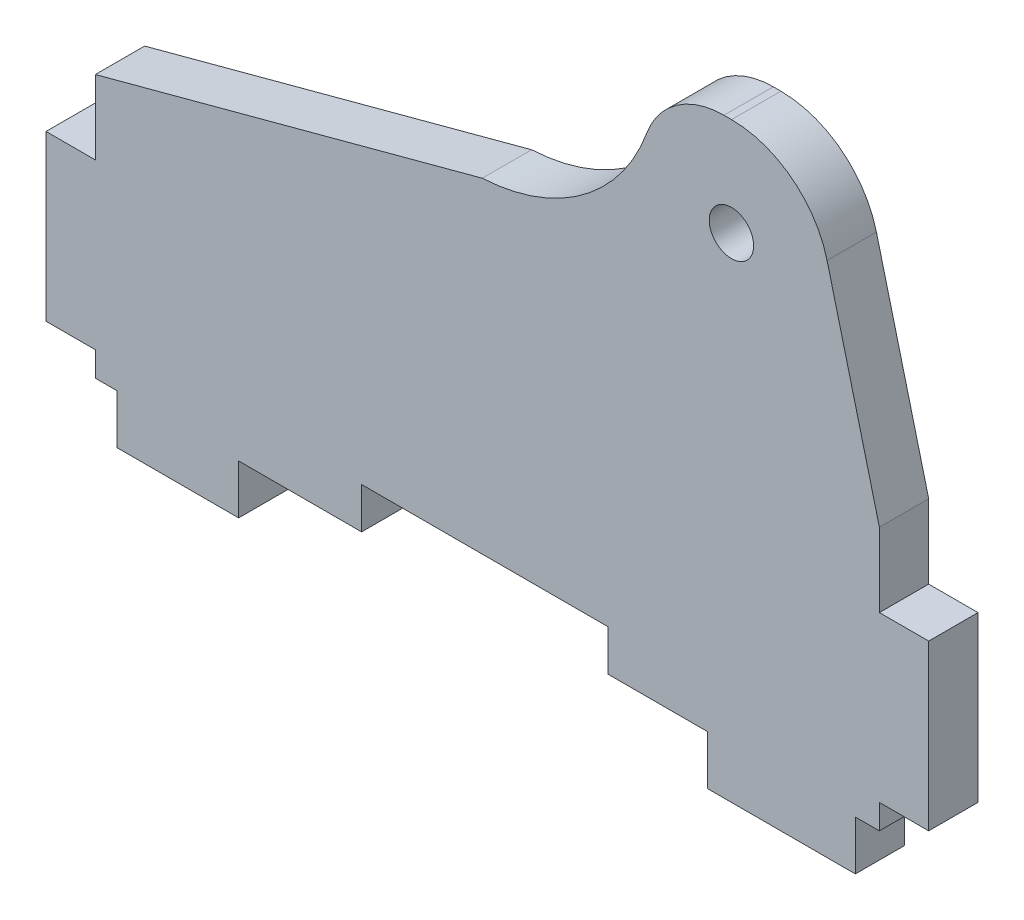
SolidWorks part; units mm, degrees
ref_plane "前视基准面" through (0, 0, 0) normal (0, 0, 1) x (1, 0, 0)
ref_plane "上视基准面" through (0, 0, 0) normal (0, 1, 0) x (1, 0, 0)
ref_plane "右视基准面" through (0, 0, 0) normal (1, 0, 0) x (0, 0, -1)
ref_plane "基准面4" through (0, 0, 0) normal (0, 0, -1) x (-1, 0, 0)
sketch "草图1" plane through (0, 0, 0) normal (0, 0, -1) x (-1, 0, 0)
  line L0 (-47.5193, 26.9593) -> (-50.6992, 14.4996)
  line L1 (-50.6992, 14.4996) -> (-50.6992, 10.0003)
  line L2 (-50.6992, 10.0003) -> (-53.6992, 10.0003)
  line L3 (-53.6992, 10.0003) -> (-53.6992, 0)
  line L4 (-53.6992, 0) -> (-50.6992, 0)
  line L5 (-50.6992, 0) -> (-50.6992, -1.5007)
  line L6 (-50.6992, -1.5007) -> (-49.2382, -1.5007)
  line L7 (-49.2382, -1.5007) -> (-49.2382, -4.5007)
  line L8 (-49.2382, -4.5007) -> (-40.2392, -4.5007)
  line L9 (-40.2392, -4.5007) -> (-40.2392, -1.4993)
  line L10 (-40.2392, -1.4993) -> (-34.2002, -1.4993)
  line L11 (-34.2002, -1.4993) -> (-34.2002, 1.0005)
  line L12 (-34.2002, 1.0005) -> (-19.2003, 1.0005)
  line L13 (-19.2003, 1.0005) -> (-19.2003, -1.4993)
  line L14 (-19.2003, -1.4993) -> (-11.7217, -1.4993)
  line L15 (-11.7217, -1.4993) -> (-11.7217, -4.5007)
  line L16 (-11.7217, -4.5007) -> (-4.3215, -4.5007)
  line L17 (-4.3215, -4.5007) -> (-4.3215, -1.5007)
  line L18 (-4.3215, -1.5007) -> (-3, -1.5007)
  line L19 (-3, -1.5007) -> (-3, 0)
  line L20 (-3, 0) -> (0, 0)
  line L21 (0, 0) -> (0, 10.0003)
  line L22 (0, 10.0003) -> (-3, 10.0003)
  line L23 (-3, 10.0003) -> (-3, 14.4996)
  line L24 (-3, 14.4996) -> (-26.5435, 20.8078)
  line L25 (-41.2462, 31.4756) -> (-41.7057, 31.4756)
  arc A0 (-41.7057, 31.4756) -> (-47.5193, 26.9593) centre (-41.7057, 25.4756) ccw
  arc A1 (-26.5435, 20.8078) -> (-36.5489, 28.1889) centre (-25.98, 32.0437) cw
  arc A2 (-36.5489, 28.1889) -> (-41.2462, 31.4756) centre (-41.2462, 26.4756) ccw
  circle A3 centre (-41.6992, 25.4997) radius 1.35
extrude "凸台-拉伸1" add sketch "草图1" against normal blind 3
